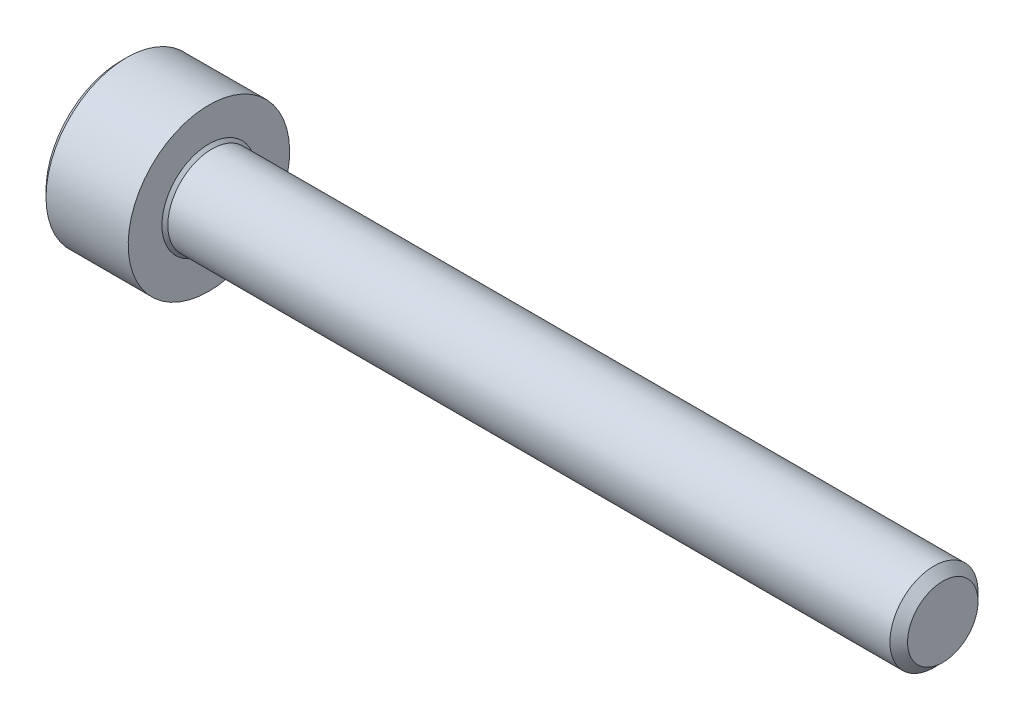
SolidWorks part; units mm, degrees
material "Galvanized Steel"
ref_plane "Front Plane" through (0, 0, 0) normal (0, 0, 1) x (1, 0, 0)
ref_plane "Top Plane" through (0, 0, 0) normal (0, 1, 0) x (1, 0, 0)
ref_plane "Right Plane" through (0, 0, 0) normal (1, 0, 0) x (0, 0, -1)
sketch "Sketch2" plane through (0, 0, 0) normal (1, 0, 0) x (0, 0, -1)
  circle A0 centre (0, 0) radius 1.5
  dimension "D1" = 3
extrude "Boss-Extrude1" add sketch "Sketch2" against normal blind 25
chamfer "Chamfer1" distance 0.3 angle 45 1 edges at (0, 0, -1.5)
sketch "Sketch6" plane through (0, 0, 0) normal (0, 0, 1) x (1, 0, 0)
  line L0 (-28, 0) -> (-28, 2.75)
  line L1 (-28, 0) -> (-25, 0)
  line L2 (-28, 2.75) -> (-25, 2.75)
  line L6 (-25, 2.75) -> (-25, 0)
  line L8 (-25, 0) -> (-14.6471, 0) construction
  line L10 (-25, 1.5) -> (-25, -1.5) construction
  dimension "D1" = 3
  dimension "D2" = 5.5
revolve "Revolve1" add sketch "Sketch6" angle 360 about L8
sketch "Sketch7" plane through (-28, 0, 0) normal (-1, 0, 0) x (0, 0, 1)
  line L1 (0, 1.4434) -> (-1.25, 0.7217)
  line L2 (-1.25, 0.7217) -> (-1.25, -0.7217)
  line L3 (-1.25, -0.7217) -> (0, -1.4434)
  line L4 (0, -1.4434) -> (1.25, -0.7217)
  line L5 (1.25, -0.7217) -> (1.25, 0.7217)
  line L6 (1.25, 0.7217) -> (0, 1.4434)
  circle A0 centre (0, 0) radius 1.25 construction
  dimension "D1" = 2.5
extrude "Cut-Extrude1" cut sketch "Sketch7" against normal blind 1.6
sketch "Sketch8" plane through (-28, 0, 0) normal (-1, 0, 0) x (0, 0, 1)
  circle A0 centre (0, 0) radius 1.4934
  dimension "D1" = 0.05
extrude "Cut-Extrude2" cut sketch "Sketch8" against normal blind 1 draft 45
chamfer "Chamfer2" distance 0.2 angle 45 1 edges at (-28, -2.75, 0)
chamfer "Chamfer3" distance 0.1 angle 45 1 edges at (-25, -1.5, 0)
